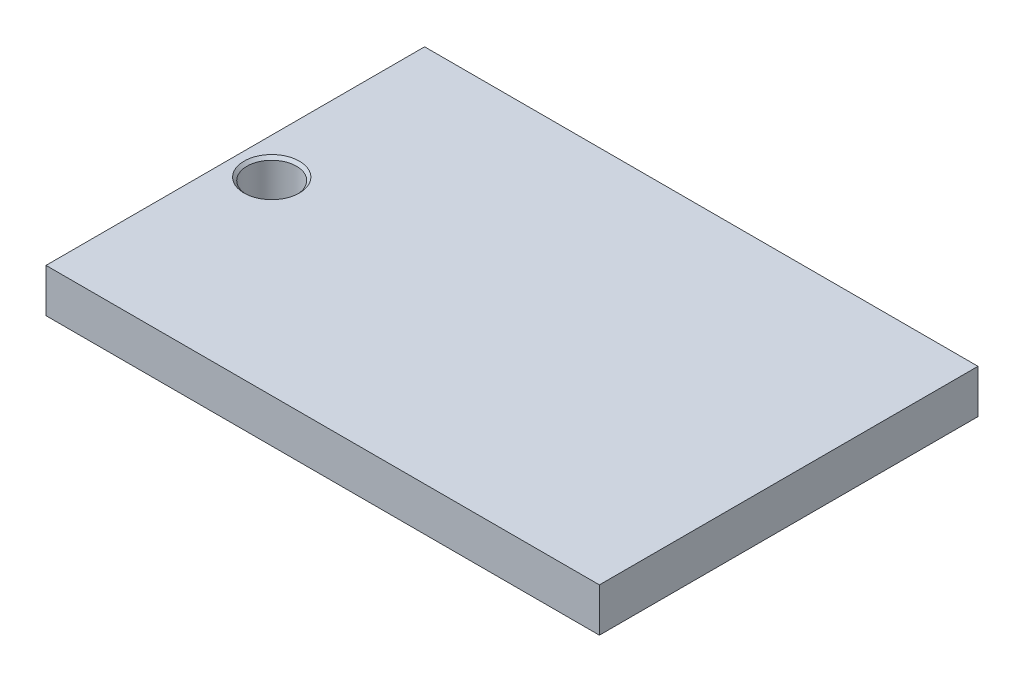
SolidWorks part; units mm, degrees
ref_plane "Front Plane" through (0, 0, 0) normal (0, 0, 1) x (1, 0, 0)
ref_plane "Top Plane" through (0, 0, 0) normal (0, 1, 0) x (1, 0, 0)
ref_plane "Right Plane" through (0, 0, 0) normal (1, 0, 0) x (0, 0, -1)
sketch "Sketch1" plane through (0, 0, 0) normal (0, 1, 0) x (1, 0, 0)
  line L1 (-24.1249, -16.5049) -> (24.1249, -16.5049)
  line L2 (-24.1249, -16.5049) -> (-24.1249, 16.5049)
  line L3 (-24.1249, 16.5049) -> (24.1249, 16.5049)
  line L4 (24.1249, -16.5049) -> (24.1249, 16.5049)
  line L5 (-24.1249, -16.5049) -> (24.1249, 16.5049) construction
  line L6 (-24.1249, 16.5049) -> (24.1249, -16.5049) construction
  point P0 (0, 0)
  dimension "D1" = 48.2498
  dimension "D2" = 33.0098
extrude "Boss-Extrude1" add sketch "Sketch1" along normal blind 3.8011
sketch "Sketch2" plane through (0, 3.8011, 0) normal (0, 1, 0) x (1, 0, 0)
  line L0 (-24.1249, 16.5049) -> (-24.1249, -16.5049) construction
  circle A0 centre (-20.9499, 0) radius 2.159
  dimension "D1" = 4.318
  dimension "D2" = 3.175
extrude "Cut-Extrude1" cut sketch "Sketch2" against normal up to next
chamfer "Chamfer1" distance 0.254 angle 45 2 edges at (-20.9499, 0, -2.159) (-20.9499, 3.8011, 2.159)
equation "\"SW\" = 1.3 - 0.0004'Slide Weidth [in]"
equation "\"SL\" = 1.9 - 0.0004'Slide Length [in]"
equation "\"SH\" = 0.15 - 0.00035'Slide Height [in]"
equation "\"Hole\"= 0.15 + 0.02'Hole Diameter [in]"
equation "\"D1@Sketch1\"=\"SL\""
equation "\"D2@Sketch1\"=\"SW\""
equation "\"D1@Boss-Extrude1\"=\"SH\""
equation "\"D1@Sketch2\"=\"Hole\""
